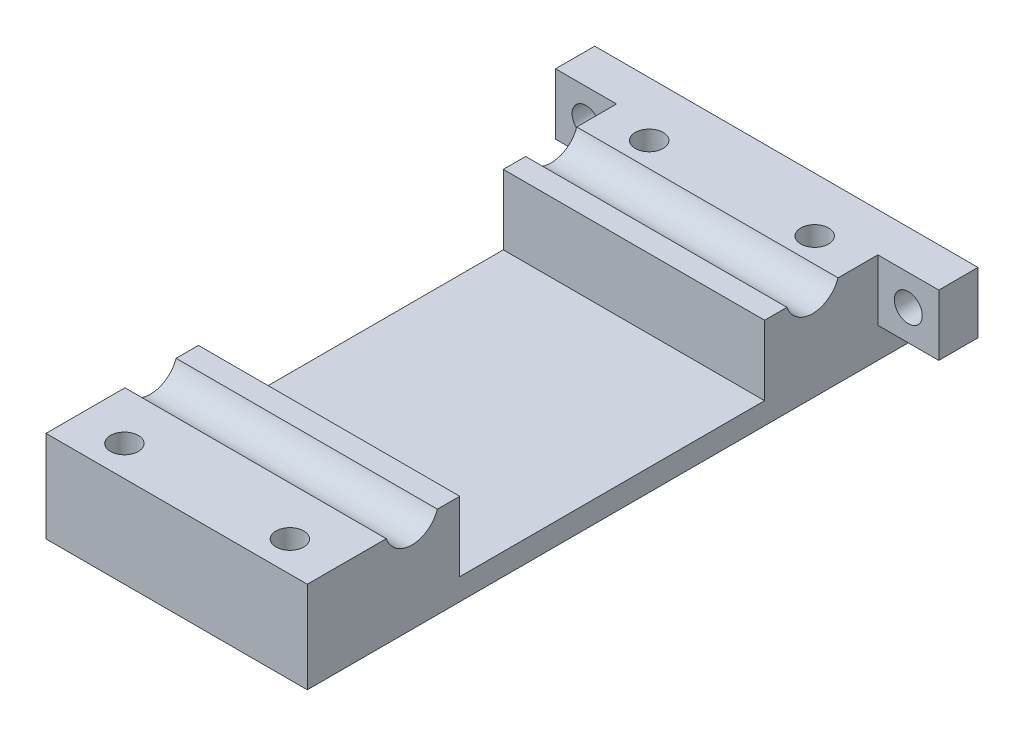
SolidWorks part; units mm, degrees
ref_plane "Front Plane" through (0, 0, 0) normal (0, 0, 1) x (1, 0, 0)
ref_plane "Top Plane" through (0, 0, 0) normal (0, 1, 0) x (1, 0, 0)
ref_plane "Right Plane" through (0, 0, 0) normal (1, 0, 0) x (0, 0, -1)
sketch "Sketch1" plane through (0, 0, 0) normal (0, 1, 0) x (1, 0, 0)
  line L1 (-15, -35) -> (15, -35)
  line L2 (-15, -35) -> (-15, 35)
  line L3 (-15, 35) -> (15, 35)
  line L4 (15, -35) -> (15, 35)
  line L5 (-15, -35) -> (15, 35) construction
  line L6 (-15, 35) -> (15, -35) construction
  point P0 (0, 0)
  dimension "D1" = 30
  dimension "D2" = 70
extrude "Boss-Extrude1" add sketch "Sketch1" along normal blind 10.5
sketch "Sketch2" plane through (0, 10.5, 0) normal (0, 1, 0) x (1, 0, 0)
  line L0 (15, -35) -> (15, 35) construction
  line L1 (-15, -17.5) -> (15, -17.5)
  line L2 (-15, -17.5) -> (-15, 17.5)
  line L3 (-15, 17.5) -> (15, 17.5)
  line L4 (15, -17.5) -> (15, 17.5)
  line L5 (-15, -17.5) -> (15, 17.5) construction
  line L6 (-15, 17.5) -> (15, -17.5) construction
  point P0 (0, 0)
  dimension "D1" = 35
extrude "Cut-Extrude1" cut sketch "Sketch2" against normal blind 8
sketch "Sketch3" plane through (15, 0, 0) normal (1, 0, 0) x (0, 0, -1)
  line L0 (-35, 10.5) -> (-17.5, 10.5) construction
  line L1 (-35, 10.5) -> (-35, 0) construction
  circle A0 centre (-23, 11.5) radius 3.1
  circle A1 centre (23, 11.5) radius 3.1
  dimension "D1" = 6.2
  dimension "D2" = 6.2
  dimension "D3" = 1
  dimension "D4" = 12
  dimension "D5" = 46
extrude "Cut-Extrude2" cut sketch "Sketch3" against normal through all
sketch "Sketch4" plane through (0, 10.5, 0) normal (0, 1, 0) x (1, 0, 0)
  line L0 (-15, 35) -> (-15, 25.9343) construction
  line L1 (15, 25.9343) -> (15, 35) construction
  line L2 (15, 35) -> (-15, 35) construction
  line L3 (-15, -35) -> (15, -35) construction
  circle A0 centre (-9.5, -31.5) radius 1.6
  circle A1 centre (9.5, -31.5) radius 1.6
  circle A2 centre (-9.5, 28.75) radius 1.6
  circle A3 centre (9.5, 28.75) radius 1.6
  dimension "D1" = 3.2
  dimension "D2" = 3.2
  dimension "D3" = 3.2
  dimension "D4" = 3.2
  dimension "D8" = 3.5
  dimension "D5" = 5.5
  dimension "D6" = 5.5
  dimension "D7" = 6.25
extrude "Cut-Extrude3" cut sketch "Sketch4" against normal through all
sketch "Sketch5" plane through (0, 0, -35) normal (0, 0, -1) x (-1, 0, 0)
  line L1 (15, 10.5) -> (22, 10.5)
  line L2 (15, 10.5) -> (15, 3.5)
  line L3 (15, 3.5) -> (22, 3.5)
  line L4 (22, 10.5) -> (22, 3.5)
  line L5 (-15, 10.5) -> (-22, 10.5)
  line L6 (-15, 10.5) -> (-15, 3.5)
  line L7 (-15, 3.5) -> (-22, 3.5)
  line L8 (-22, 10.5) -> (-22, 3.5)
  dimension "D1" = 7
  dimension "D2" = 7
  dimension "D3" = 7
  dimension "D4" = 7
extrude "Boss-Extrude2" add sketch "Sketch5" against normal blind 4.5
sketch "Sketch6" plane through (0, 0, -35) normal (0, 0, -1) x (-1, 0, 0)
  line L0 (22, 3.5) -> (22, 10.5) construction
  line L1 (15, 3.5) -> (22, 3.5) construction
  line L2 (-22, 10.5) -> (-22, 3.5) construction
  circle A0 centre (-18.5, 7) radius 1.6
  circle A1 centre (18.5, 7) radius 1.6
  dimension "D2" = 3.5
  dimension "D3" = 3.5
  dimension "D4" = 3.2
  dimension "D5" = 3.2
  dimension "D1" = 3.5
extrude "Cut-Extrude4" cut sketch "Sketch6" against normal up to next
